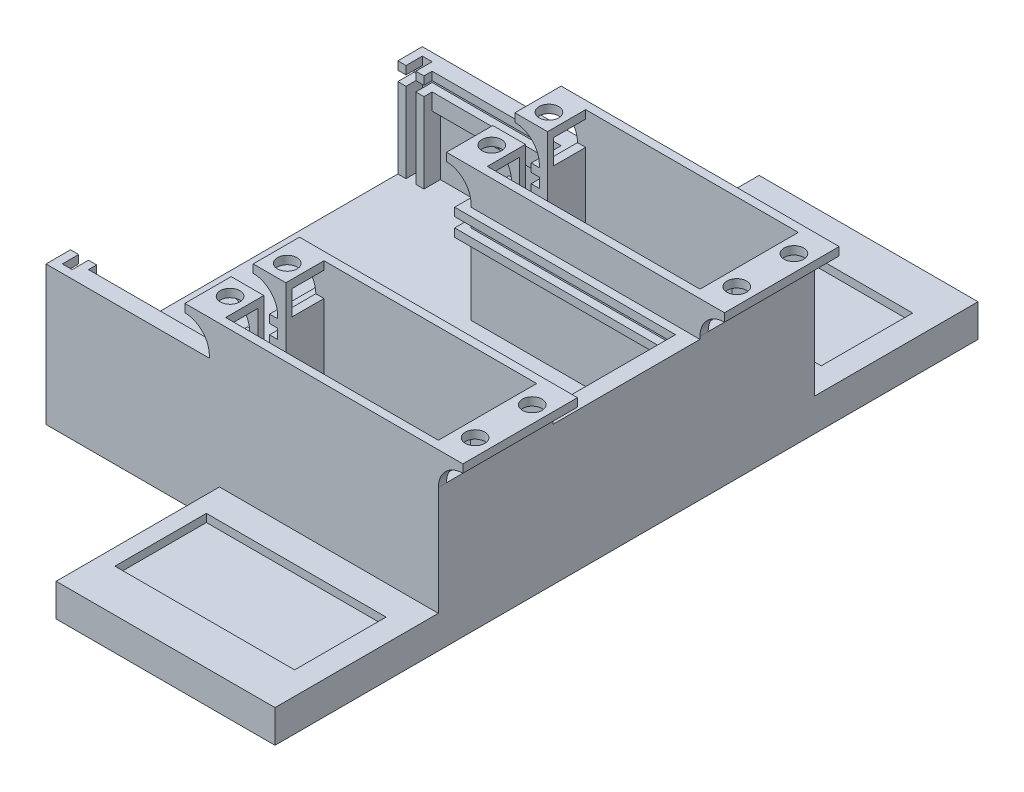
SolidWorks part; units mm, degrees
ref_plane "Plan de face" through (0, 0, 0) normal (0, 0, 1) x (1, 0, 0)
ref_plane "Plan de dessus" through (0, 0, 0) normal (0, 1, 0) x (1, 0, 0)
ref_plane "Plan de droite" through (0, 0, 0) normal (1, 0, 0) x (0, 0, -1)
sketch "Esquisse1" plane through (0, 0, 0) normal (0, 1, 0) x (1, 0, 0)
  line L1 (0, 0) -> (120.1, 0)
  line L2 (0, 0) -> (0, -115.2)
  line L3 (0, -115.2) -> (120.1, -115.2)
  line L4 (120.1, 0) -> (120.1, -115.2)
extrude "Boss.-Extru.1" add sketch "Esquisse1" along normal blind 12.57
sketch "Esquisse2" plane through (0, 12.57, 0) normal (0, 1, 0) x (1, 0, 0)
  line L1 (120.1, 0) -> (50, 0)
  line L2 (120.1, 0) -> (120.1, -35.1)
  line L3 (120.1, -35.1) -> (50, -35.1)
  line L4 (50, 0) -> (50, -35.1)
extrude "Boss.-Extru.2" add sketch "Esquisse2" along normal blind 0.01
sketch "Esquisse3" plane through (0, 12.58, 0) normal (0, 1, 0) x (1, 0, 0)
  line L0 (120.1, 0) -> (50, 0) construction
  line L1 (52.5, -2.5) -> (117.6, -2.5)
  line L2 (52.5, -2.5) -> (52.5, -32.6)
  line L3 (52.5, -32.6) -> (117.6, -32.6)
  line L4 (117.6, -2.5) -> (117.6, -32.6)
  line L5 (120.1, -35.1) -> (120.1, 0) construction
  line L6 (50, -35.1) -> (120.1, -35.1) construction
  line L7 (50, 0) -> (50, -35.1) construction
  line L9 (50, 0) -> (120.1, 0)
  line L10 (50, 0) -> (50, -35.1)
  line L11 (50, -35.1) -> (120.1, -35.1)
  line L12 (120.1, 0) -> (120.1, -35.1)
  dimension "D1" = 2.5
  dimension "D2" = 2.5
  dimension "D3" = 2.5
  dimension "D4" = 2.5
extrude "Boss.-Extru.3" add sketch "Esquisse3" along normal blind 40.8
sketch "Esquisse4" plane through (0, 12.57, 0) normal (0, 1, 0) x (1, 0, 0)
  line L1 (50, -80.1) -> (120.1, -80.1)
  line L2 (50, -80.1) -> (50, -115.2)
  line L3 (50, -115.2) -> (120.1, -115.2)
  line L4 (120.1, -80.1) -> (120.1, -115.2)
  line L5 (52.5, -82.6) -> (117.6, -82.6)
  line L6 (52.5, -82.6) -> (52.5, -112.7)
  line L7 (52.5, -112.7) -> (117.6, -112.7)
  line L8 (117.6, -82.6) -> (117.6, -112.7)
  dimension "D1" = 2.5
  dimension "2.5" = 2.5
  dimension "D2" = 2.5
  dimension "D3" = 2.5
  dimension "D4" = 65.1
  dimension "D5" = 30.1
extrude "Boss.-Extru.4" add sketch "Esquisse4" along normal blind 40.8
sketch "Esquisse5" plane through (0, 0, 115.2) normal (0, 0, 1) x (1, 0, 0)
  line L0 (0, 0) -> (120.1, 0) construction
  line L1 (53.1, 10) -> (120.1, 10)
  line L2 (53.1, 10) -> (53.1, 0)
  line L3 (53.1, 0) -> (120.1, 0)
  line L4 (120.1, 10) -> (120.1, 0)
  line L6 (120.1, 53.37) -> (120.1, 0) construction
  dimension "D1" = 67
extrude "Boss.-Extru.5" add sketch "Esquisse5" along normal blind 50
sketch "Esquisse6" plane through (0, 12.57, 0) normal (0, 1, 0) x (1, 0, 0)
  line L0 (120.1, -165.2) -> (120.1, -115.2) construction
  line L1 (58.1, -124.2) -> (113.1, -124.2)
  line L2 (58.1, -124.2) -> (58.1, -152.2)
  line L3 (58.1, -152.2) -> (113.1, -152.2)
  line L4 (113.1, -124.2) -> (113.1, -152.2)
  line L7 (120.1, -165.2) -> (53.1, -165.2) construction
  dimension "D1" = 28
  dimension "55.88" = 55
  dimension "D2" = 7
  dimension "D3" = 13
extrude "Enlèv. mat.-Extru.1" cut sketch "Esquisse6" against normal blind 5
ref_plane "Plan6" through (0, 0, 57.6) normal (0, 0, -1) x (-1, 0, 0)
mirror "Symétrie1" about plane through (0, 0, 57.6) normal (0, 0, -1) of "Enlèv. mat.-Extru.1", "Boss.-Extru.5"
sketch "Esquisse8" plane through (0, 0, 0) normal (0, 0, -1) x (-1, 0, 0)
  line L0 (-50, 53.38) -> (-42.5, 53.38)
  line L1 (-50, 53.38) -> (-50, 12.57) construction
  line L2 (-50, 53.38) -> (-50, 43.38)
  line L3 (-42.5, 53.38) -> (-42.5, 50.88)
  arc A0 (-50, 43.38) -> (-42.5, 50.88) centre (-42.5, 43.38) cw
  dimension "D1" = 7.5
  dimension "D2" = 2.5
  dimension "D3" = 7.5
extrude "Boss.-Extru.6" add sketch "Esquisse8" against normal blind 35.1
sketch "Esquisse10" plane through (0, 53.38, 0) normal (0, 1, 0) x (1, 0, 0)
  line L0 (42.5, -35.1) -> (120.1, -35.1) construction
  line L3 (42.5, -35.1) -> (42.5, 0) construction
  circle A0 centre (47.55, -8.8) radius 3
  circle A1 centre (47.55, -26.3) radius 3
  point P7 (47.4883, -17.5502)
  dimension "D1" = 6
  dimension "D2" = 6
  dimension "D3" = 17.5
  dimension "D4" = 8.8
  dimension "D5" = 5.05
  dimension "D6" = 5.05
extrude "Enlèv. mat.-Extru.2" cut sketch "Esquisse10" against normal blind 2.5
ref_plane "Plan7" through (85.05, 0, 0) normal (-1, 0, 0) x (0, 0, 1)
mirror "Symétrie2" about plane through (85.05, 0, 0) normal (-1, 0, 0) of "Boss.-Extru.6", "Enlèv. mat.-Extru.2"
sketch "Esquisse11" plane through (0, 0, 115.2) normal (0, 0, 1) x (1, 0, 0)
  line L0 (50, 43.37) -> (50, 53.37)
  line L2 (42.5, 53.37) -> (50, 53.37)
  line L3 (42.5, 53.37) -> (42.5, 50.87)
  line L4 (50, 53.37) -> (50, 12.57) construction
  line L5 (50, 53.37) -> (120.1, 53.37) construction
  arc A1 (50, 43.37) -> (42.5, 50.87) centre (42.5, 43.37) ccw
  dimension "D2" = 7.5
  dimension "D1" = 7.5
  dimension "D3" = 2.5
extrude "Boss.-Extru.7" add sketch "Esquisse11" against normal blind 35.1
sketch "Esquisse12" plane through (0, 53.37, 0) normal (0, 1, 0) x (1, 0, 0)
  line L0 (42.5, -80.1) -> (42.5, -115.2) construction
  line L1 (42.5, -115.2) -> (120.1, -115.2) construction
  line L2 (120.1, -80.1) -> (42.5, -80.1) construction
  circle A0 centre (47.55, -88.9) radius 3
  circle A1 centre (47.55, -106.4) radius 3
  dimension "D2" = 6
  dimension "D3" = 6
  dimension "D1" = 17.5
  dimension "D4" = 5.05
  dimension "D5" = 5.05
  dimension "D6" = 8.8
  dimension "D7" = 8.8
extrude "Enlèv. mat.-Extru.3" cut sketch "Esquisse12" against normal blind 2.5
sketch "Esquisse13" plane through (50, 0, 0) normal (-1, 0, 0) x (0, 0, 1)
  line L0 (80.1, 43.37) -> (115.2, 43.37) construction
  line L1 (82.6, 50.87) -> (92.47, 50.87)
  line L2 (82.6, 50.87) -> (82.6, 43.37)
  line L3 (82.6, 43.37) -> (92.47, 43.37)
  line L4 (92.47, 50.87) -> (92.47, 43.37)
  line L5 (80.1, 43.37) -> (115.2, 43.37) construction
  line L6 (102.83, 50.87) -> (112.7, 50.87)
  line L7 (102.83, 50.87) -> (102.83, 43.37)
  line L8 (102.83, 43.37) -> (112.7, 43.37)
  line L9 (112.7, 50.87) -> (112.7, 43.37)
  line L10 (80.1, 50.87) -> (80.1, 43.37) construction
  line L11 (115.2, 43.37) -> (115.2, 50.87) construction
  line L12 (80.1, 50.87) -> (115.2, 50.87) construction
  dimension "D1" = 2.5
  dimension "D2" = 9.87
  dimension "D3" = 2.5
  dimension "D4" = 9.87
extrude "Enlèv. mat.-Extru.6" cut sketch "Esquisse13" against normal up to next and the other way up to next
sketch "Esquisse14" plane through (50, 0, 0) normal (-1, 0, 0) x (0, 0, 1)
  line L1 (2.5, 50.88) -> (12.37, 50.88)
  line L2 (2.5, 50.88) -> (2.5, 43.38)
  line L3 (2.5, 43.38) -> (12.37, 43.38)
  line L4 (12.37, 50.88) -> (12.37, 43.38)
  line L5 (22.73, 50.88) -> (32.6, 50.88)
  line L6 (22.73, 50.88) -> (22.73, 43.38)
  line L7 (22.73, 43.38) -> (32.6, 43.38)
  line L8 (32.6, 50.88) -> (32.6, 43.38)
  line L10 (35.1, 50.88) -> (0, 50.88) construction
  line L11 (0, -55) -> (0, 55) construction
  line L12 (35.1, 43.38) -> (35.1, 50.88) construction
  dimension "D1" = 7.5
  dimension "D2" = 9.87
  dimension "D3" = 7.5
  dimension "D4" = 9.87
  dimension "D5" = 2.5
  dimension "D6" = 2.5
  dimension "D7" = 2.5
extrude "Enlèv. mat.-Extru.7" cut sketch "Esquisse14" against normal up to next and the other way up to next
sketch "Esquisse15" plane through (50, 0, 0) normal (-1, 0, 0) x (0, 0, 1)
  line L1 (14.175, 12.58) -> (20.925, 12.58)
  line L2 (14.175, 12.58) -> (14.175, 53.38)
  line L3 (14.175, 53.38) -> (20.925, 53.38)
  line L4 (20.925, 12.58) -> (20.925, 53.38)
  line L6 (22.73, 43.38) -> (22.73, 50.88) construction
  line L7 (12.37, 50.88) -> (12.37, 43.38) construction
  line L8 (2.5, 12.58) -> (32.6, 12.58) construction
  line L9 (35.1, 53.38) -> (0, 53.38) construction
  dimension "D1" = 6.75
  dimension "D2" = 1.805
  dimension "D3" = 1.805
extrude "Enlèv. mat.-Extru.8" cut sketch "Esquisse15" against normal up to next and the other way up to next
sketch "Esquisse16" plane through (50, 0, 0) normal (-1, 0, 0) x (0, 0, 1)
  line L0 (92.47, 50.87) -> (92.47, 43.37) construction
  line L1 (94.275, 53.37) -> (101.025, 53.37)
  line L2 (94.275, 53.37) -> (94.275, 12.57)
  line L3 (94.275, 12.57) -> (101.025, 12.57)
  line L4 (101.025, 53.37) -> (101.025, 12.57)
  line L5 (80.1, 12.57) -> (115.2, 12.57) construction
  line L7 (102.83, 43.37) -> (102.83, 50.87) construction
  line L8 (80.1, 53.37) -> (115.2, 53.37) construction
  dimension "D1" = 6.75
  dimension "D2" = 1.805
  dimension "D3" = 1.805
extrude "Enlèv. mat.-Extru.9" cut sketch "Esquisse16" against normal up to next and the other way up to next
mirror "Symétrie3" about plane through (85.05, 0, 0) normal (-1, 0, 0) of "Enlèv. mat.-Extru.6", "Enlèv. mat.-Extru.3", "Boss.-Extru.7", "Enlèv. mat.-Extru.7"
sketch "Esquisse17" plane through (0, 12.57, 0) normal (0, 1, 0) x (1, 0, 0)
  line L1 (117.6, -35.1) -> (120.1, -35.1)
  line L2 (117.6, -35.1) -> (117.6, -57.6)
  line L3 (117.6, -57.6) -> (120.1, -57.6)
  line L4 (120.1, -35.1) -> (120.1, -57.6)
  line L6 (50, -35.1) -> (120.1, -35.1) construction
  line L8 (120.1, -80.1) -> (120.1, -35.1) construction
  dimension "D1" = 2.5
  dimension "D2" = 22.5
extrude "Boss.-Extru.8" add sketch "Esquisse17" along normal blind 30
sketch "Esquisse18" plane through (0, 12.57, 0) normal (0, 1, 0) x (1, 0, 0)
  line L1 (0, 0) -> (50, 0)
  line L2 (0, 0) -> (0, -2.5)
  line L3 (0, -2.5) -> (50, -2.5)
  line L4 (50, 0) -> (50, -2.5)
  line L5 (50, 0) -> (50, -35.1) construction
  dimension "D1" = 2.5
extrude "Boss.-Extru.9" add sketch "Esquisse18" along normal blind 30
sketch "Esquisse19" plane through (117.6, 0, 0) normal (-1, 0, 0) x (0, 0, 1)
  line L0 (57.6, 42.57) -> (57.6, 12.57) construction
  line L1 (57.6, 34.57) -> (35.1, 34.57)
  line L2 (57.6, 34.57) -> (57.6, 37.07)
  line L3 (57.6, 37.07) -> (35.1, 37.07)
  line L4 (35.1, 34.57) -> (35.1, 37.07)
  line L5 (35.1, 42.57) -> (35.1, 12.57) construction
  line L7 (35.1, 40.07) -> (57.6, 40.07)
  line L8 (35.1, 40.07) -> (35.1, 42.57)
  line L9 (35.1, 42.57) -> (57.6, 42.57)
  line L10 (57.6, 40.07) -> (57.6, 42.57)
  line L12 (35.1, 12.57) -> (57.6, 12.57) construction
  line L13 (35.1, 42.57) -> (57.6, 42.57) construction
  dimension "D1" = 2.5
  dimension "D2" = 2.5
  dimension "D3" = 22
  dimension "D4" = 3
extrude "Boss.-Extru.10" add sketch "Esquisse19" along normal blind 2.5
sketch "Esquisse21" plane through (0, 0, 35.1) normal (0, 0, 1) x (1, 0, 0)
  line L0 (115.1, 37.07) -> (115.1, 34.57) construction
  line L1 (115.1, 42.57) -> (50, 42.57)
  line L2 (115.1, 42.57) -> (115.1, 40.07)
  line L3 (115.1, 40.07) -> (50, 40.07)
  line L4 (50, 42.57) -> (50, 40.07)
  line L5 (115.1, 37.07) -> (50, 37.07)
  line L6 (115.1, 37.07) -> (115.1, 34.57)
  line L7 (115.1, 34.57) -> (50, 34.57)
  line L8 (50, 37.07) -> (50, 34.57)
  line L9 (50, 43.38) -> (50, 12.57) construction
  dimension "D1" = 2.5
  dimension "D2" = 3
  dimension "D3" = 2.5
sketch "Esquisse22" plane through (50, 0, 0) normal (-1, 0, 0) x (0, 0, 1)
  line L0 (57.6, 37.07) -> (35.1, 37.07) construction
  line L1 (37.6, 42.57) -> (20.925, 42.57)
  line L2 (37.6, 42.57) -> (37.6, 40.07)
  line L3 (37.6, 40.07) -> (20.925, 40.07)
  line L4 (20.925, 42.57) -> (20.925, 40.07)
  line L5 (20.925, 12.58) -> (20.925, 43.38) construction
  line L6 (37.6, 37.07) -> (20.925, 37.07)
  line L7 (14.175, 37.07) -> (2.5, 37.07)
  line L8 (14.175, 37.07) -> (14.175, 34.57)
  line L9 (14.175, 34.57) -> (2.5, 34.57)
  line L10 (2.5, 37.07) -> (2.5, 34.57)
  line L11 (2.5, 42.57) -> (2.5, 12.57) construction
  line L12 (14.175, 43.38) -> (14.175, 12.58) construction
  line L13 (2.5, 42.57) -> (14.175, 42.57)
  line L14 (2.5, 42.57) -> (2.5, 40.07)
  line L15 (2.5, 40.07) -> (14.175, 40.07)
  line L16 (14.175, 42.57) -> (14.175, 40.07)
  line L17 (37.6, 37.07) -> (37.6, 34.57)
  line L18 (2.5, 12.57) -> (35.1, 12.57) construction
  line L19 (37.6, 34.57) -> (20.925, 34.57)
  line L20 (35.1, 42.57) -> (35.1, 40.07) construction
  line L21 (20.925, 37.07) -> (20.925, 34.57)
  line L23 (35.1, 37.07) -> (35.1, 34.57) construction
  point P22 (37.6, 41.32)
  dimension "D1" = 2.5
  dimension "D2" = 2.5
  dimension "D3" = 30
  dimension "D4" = 2.5
  dimension "D5" = 3
  dimension "D6" = 2.5
  dimension "D7" = 2.5
  dimension "D8" = 2.5
extrude "Boss.-Extru.11" add sketch "Esquisse21" along normal blind 2.5
extrude "Boss.-Extru.13" add sketch "Esquisse22" along normal blind 2.5
sketch "Esquisse25" plane through (0, 0, 2.5) normal (0, 0, 1) x (1, 0, 0)
  line L1 (47.5, 42.57) -> (5.5, 42.57)
  line L2 (47.5, 42.57) -> (47.5, 40.07)
  line L3 (47.5, 40.07) -> (5.5, 40.07)
  line L4 (5.5, 42.57) -> (5.5, 40.07)
  line L5 (47.5, 40.07) -> (115.1, 40.07) construction
  line L6 (47.5, 37.07) -> (5.5, 37.07)
  line L7 (47.5, 37.07) -> (47.5, 32)
  line L9 (5.5, 37.07) -> (5.5, 32)
  line L11 (0, -55) -> (0, 55) construction
  line L12 (0, 42.57) -> (2.5, 42.57)
  line L13 (0, 42.57) -> (0, 40.07)
  line L14 (0, 40.07) -> (2.5, 40.07)
  line L15 (2.5, 42.57) -> (2.5, 40.07)
  line L16 (0, 42.57) -> (47.5, 42.57) construction
  line L17 (0, 37.07) -> (2.5, 37.07)
  line L18 (0, 37.07) -> (0, 10)
  line L19 (0, 10) -> (2.5, 10)
  line L20 (2.5, 37.07) -> (2.5, 10)
  line L21 (120.1, 10) -> (53.1, 10) construction
  line L22 (0, 12.57) -> (50, 12.57) construction
  line L23 (5.5, 12.57) -> (8, 12.57)
  line L24 (5.5, 12.57) -> (5.5, 32)
  line L26 (8, 12.57) -> (8, 32)
  line L27 (8, 32) -> (47.5, 32)
  dimension "D1" = 2.5
  dimension "D2" = 2.5
  dimension "D3" = 2.5
  dimension "D4" = 2.5
  dimension "D5" = 3
  dimension "D6" = 3
  dimension "D7" = 3
extrude "Boss.-Extru.15" add sketch "Esquisse25" along normal blind 2.5
sketch "Esquisse27" plane through (0, 0, 5) normal (0, 0, 1) x (1, 0, 0)
  line L0 (0, -55) -> (0, 55) construction
  line L1 (2.5, 42.57) -> (0, 42.57)
  line L2 (2.5, 42.57) -> (2.5, 40.07)
  line L3 (2.5, 40.07) -> (0, 40.07)
  line L4 (0, 42.57) -> (0, 40.07)
  line L5 (0, 40.07) -> (2.5, 40.07) construction
  line L6 (5.5, 40.07) -> (50, 40.07) construction
  line L7 (5.5, 42.57) -> (8, 42.57)
  line L8 (5.5, 42.57) -> (5.5, 40.07)
  line L9 (5.5, 40.07) -> (8, 40.07)
  line L10 (8, 42.57) -> (8, 40.07)
  line L11 (2.5, 37.07) -> (0, 37.07) construction
  line L12 (5.5, 37.07) -> (8, 37.07)
  line L13 (5.5, 37.07) -> (5.5, 12.57)
  line L14 (5.5, 12.57) -> (8, 12.57)
  line L15 (8, 37.07) -> (8, 12.57)
  line L16 (2.5, 12.57) -> (0, 12.57)
  line L17 (2.5, 12.57) -> (2.5, 37.07)
  line L18 (2.5, 37.07) -> (0, 37.07)
  line L19 (0, 12.57) -> (0, 37.07)
  dimension "D1" = 2.5
extrude "Boss.-Extru.16" add sketch "Esquisse27" along normal blind 2.5
mirror "Symétrie5" about plane through (0, 0, 57.6) normal (0, 0, -1) of "Boss.-Extru.16", "Boss.-Extru.15", "Boss.-Extru.10", "Boss.-Extru.9", "Boss.-Extru.8", "Boss.-Extru.13", "Boss.-Extru.11"
